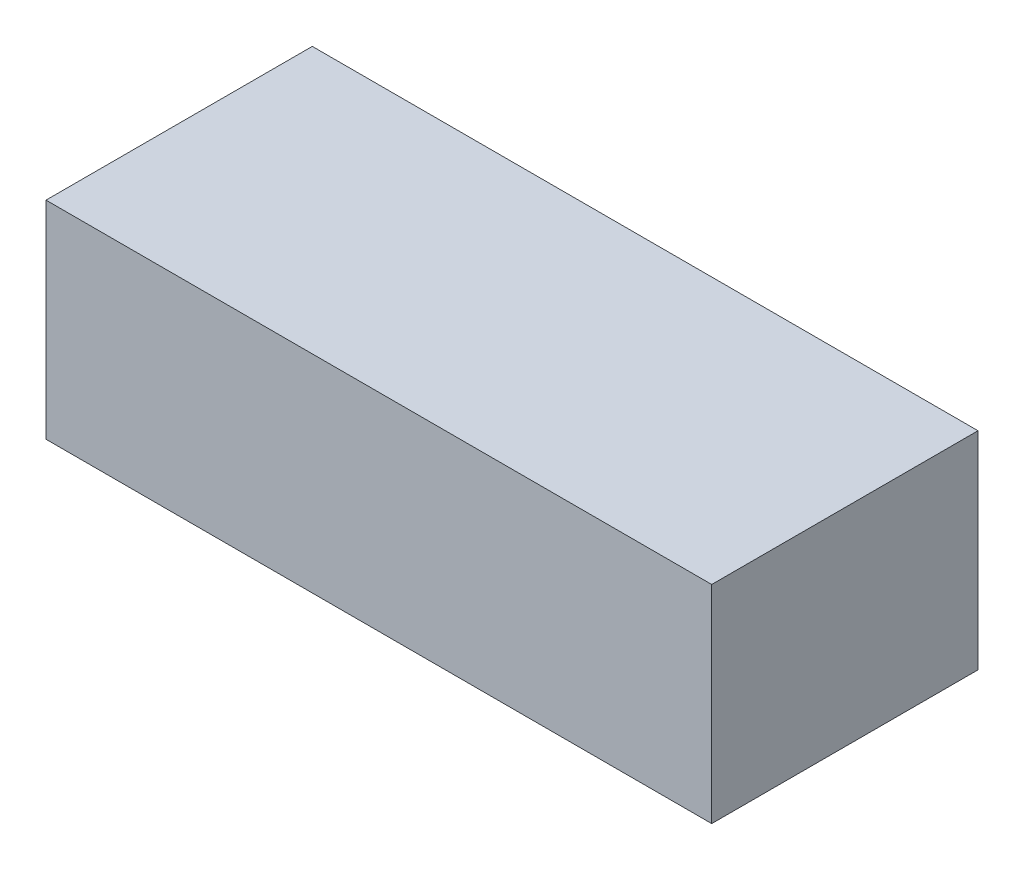
SolidWorks part; units mm, degrees
ref_plane "Front Plane" through (0, 0, 0) normal (0, 0, 1) x (1, 0, 0)
ref_plane "Top Plane" through (0, 0, 0) normal (0, 1, 0) x (1, 0, 0)
ref_plane "Right Plane" through (0, 0, 0) normal (1, 0, 0) x (0, 0, -1)
sketch "Sketch1" plane through (0, 0, 0) normal (0, 1, 0) x (1, 0, 0)
  line L1 (-112.5, -45) -> (112.5, -45)
  line L2 (-112.5, -45) -> (-112.5, 45)
  line L3 (-112.5, 45) -> (112.5, 45)
  line L4 (112.5, -45) -> (112.5, 45)
  line L5 (-112.5, -45) -> (112.5, 45) construction
  line L6 (-112.5, 45) -> (112.5, -45) construction
  point P0 (0, 0)
  dimension "D1" = 225
  dimension "D2" = 90
extrude "Boss-Extrude1" add sketch "Sketch1" along normal blind 70
ref_plane "Plane1" [suppressed] through (162.5, 0, 0) normal (1, 0, 0) x (0, 0, -1)
sketch "Sketch2" plane through (112.5, 0, 0) normal (1, 0, 0) x (0, 0, -1)
  line L0 (-45, 70) -> (45, 70) construction
  line L1 (-45, 70) -> (-45, 0) construction
  circle A0 centre (-31, 56) radius 1.5
  circle A1 centre (-27.5, 56) radius 1.5
  circle A2 centre (-24, 56) radius 1.5
  dimension "D3" = 3
  dimension "D1" = 14
  dimension "D2" = 14
  dimension "D5" = 3.5
  dimension "D4" = 3
sketch "Sketch3" [suppressed] plane through (162.5, 0, 0) normal (1, 0, 0) x (0, 0, -1)
  circle A2 centre (23.2369, 16.9273) radius 1.5
sketch3d "3DSketch2" [suppressed]
  spline S0 degree 3 poles (112.5, 56, 24) (172.628, 101.4263, -1.0264) (109.0806, -18.8897, 41.0307) (162.5, 16.9273, -23.2369) knots 0 0 0 0 1 1 1 1
sweep "Sweep1" [suppressed] add profiles "Sketch2" path "3DSketch2"
